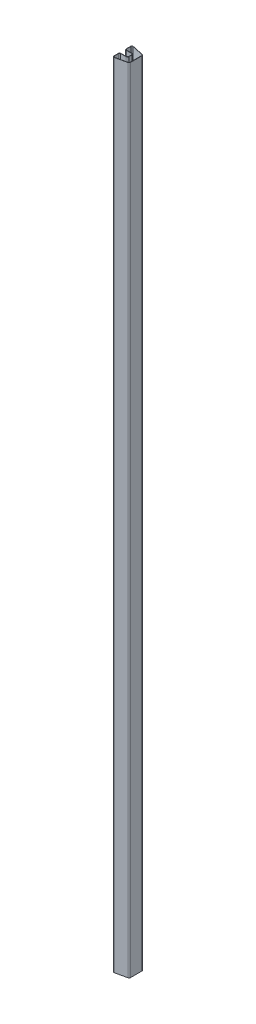
SolidWorks part; units mm, degrees
ref_plane "Front Plane" through (0, 0, 0) normal (0, 0, 1) x (1, 0, 0)
ref_plane "Top Plane" through (0, 0, 0) normal (0, 1, 0) x (1, 0, 0)
ref_plane "Right Plane" through (0, 0, 0) normal (1, 0, 0) x (0, 0, -1)
sketch "Sketch1" plane through (0, 0, 0) normal (0, 1, 0) x (1, 0, 0)
  line L0 (62.4977, -33.3724) -> (51.9977, -31.0446)
  line L1 (51.9977, -31.0446) -> (51.9977, -36.5446)
  line L2 (51.9977, -36.5446) -> (57.9977, -36.5446)
  line L3 (57.9977, -36.5446) -> (57.9977, -40.5446)
  line L4 (57.9977, -40.5446) -> (51.9977, -40.5446)
  line L5 (51.9977, -40.5446) -> (51.9977, -46.0446)
  line L6 (51.9977, -46.0446) -> (62.4977, -43.7168)
  line L7 (62.4977, -43.7168) -> (62.4977, -33.3724)
  point P10 (57.9977, -38.5446)
  point P11 (62.4977, -38.5446)
  dimension "D1" = 90
  dimension "D2" = 90
  dimension "D3" = 90
  dimension "D4" = 90
  dimension "D5" = 77.5
  dimension "D6" = 77.5
  dimension "D7" = 6
  dimension "D8" = 4
  dimension "D9" = 5.5
  dimension "D10" = 5.5
  dimension "D11" = 6
  dimension "D12" = 4.5
  dimension "D13" = 10.3444
extrude "Boss-Extrude1" add sketch "Sketch1" along normal blind 600
fillet "Fillet1" radius 1 8 edges at (57.9977, 300, 40.5446) (51.9977, 300, 46.0446) (51.9977, 300, 40.5446) (57.9977, 300, 36.5446) (51.9977, 300, 36.5446) (51.9977, 300, 31.0446) (62.4977, 300, 33.3724) (62.4977, 300, 43.7168)
shell "Shell3" thickness 0.2
